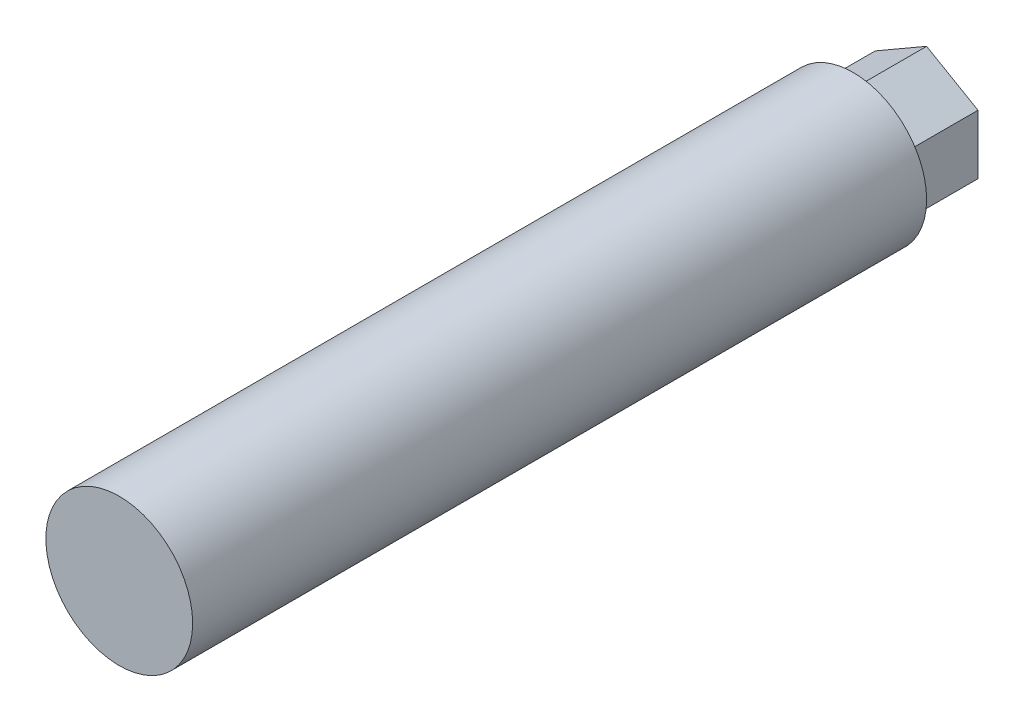
SolidWorks part; units mm, degrees
ref_plane "Front Plane" through (0, 0, 0) normal (0, 0, 1) x (1, 0, 0)
ref_plane "Top Plane" through (0, 0, 0) normal (0, 1, 0) x (1, 0, 0)
ref_plane "Right Plane" through (0, 0, 0) normal (1, 0, 0) x (0, 0, -1)
sketch "Sketch1" plane through (0, 0, 0) normal (0, 0, 1) x (1, 0, 0)
  circle A0 centre (0, 0) radius 5
  dimension "D1" = 10
extrude "Boss-Extrude1" add sketch "Sketch1" along normal blind 50
sketch "Sketch2" plane through (0, 0, 0) normal (0, 0, -1) x (-1, 0, 0)
  line L1 (0, 4.0415) -> (-3.5, 2.0207)
  line L2 (-3.5, 2.0207) -> (-3.5, -2.0207)
  line L3 (-3.5, -2.0207) -> (0, -4.0415)
  line L4 (0, -4.0415) -> (3.5, -2.0207)
  line L5 (3.5, -2.0207) -> (3.5, 2.0207)
  line L6 (3.5, 2.0207) -> (0, 4.0415)
  circle A0 centre (0, 0) radius 3.5 construction
  dimension "D1" = 7
extrude "Boss-Extrude2" add sketch "Sketch2" along normal blind 5
chamfer "Chamfer1" [suppressed] distance 1 angle 45
chamfer "Chamfer2" [suppressed] distance 1 angle 45
chamfer "Chamfer3" [suppressed] distance 1 angle 45
chamfer "Chamfer4" [suppressed] distance 1 angle 45
chamfer "Chamfer5" [suppressed] distance 1 angle 45
chamfer "Chamfer6" [suppressed] distance 1 angle 45
